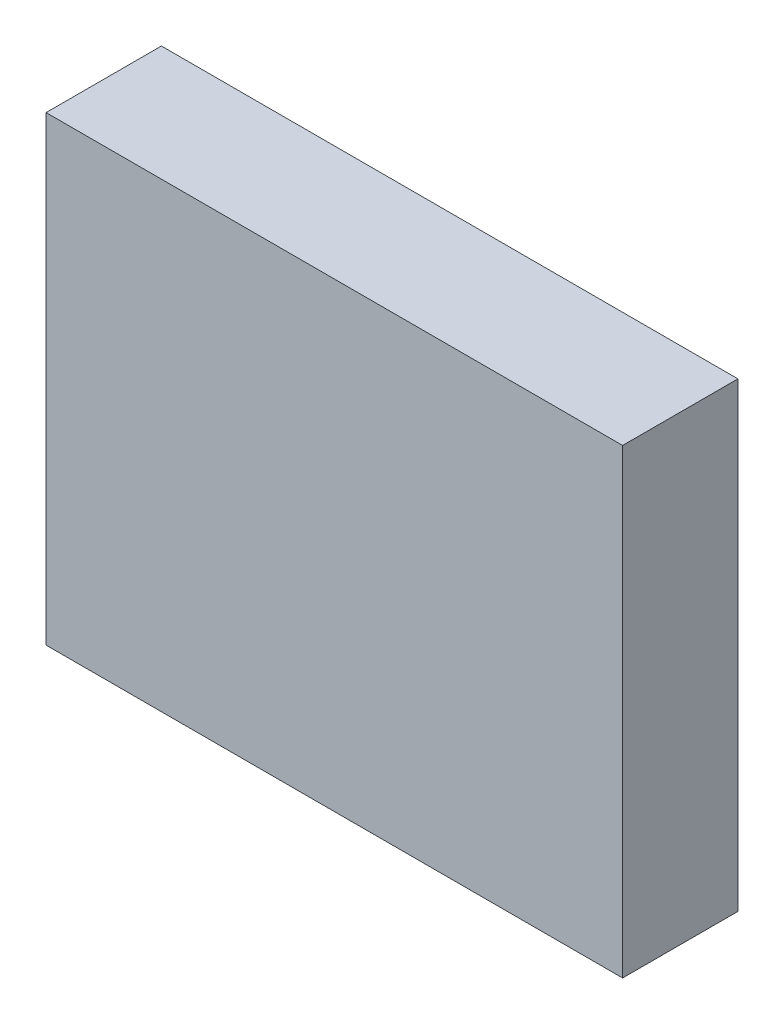
SolidWorks part; units mm, degrees
ref_plane "Front Plane" through (0, 0, 0) normal (0, 0, 1) x (1, 0, 0)
ref_plane "Top Plane" through (0, 0, 0) normal (0, 1, 0) x (1, 0, 0)
ref_plane "Right Plane" through (0, 0, 0) normal (1, 0, 0) x (0, 0, -1)
sketch "Sketch1" plane through (0, 0, 0) normal (0, 0, 1) x (1, 0, 0)
  line L1 (25, -20) -> (-25, -20)
  line L2 (25, -20) -> (25, 20)
  line L3 (25, 20) -> (-25, 20)
  line L4 (-25, -20) -> (-25, 20)
  line L5 (25, -20) -> (-25, 20) construction
  line L6 (25, 20) -> (-25, -20) construction
  point P0 (0, 0)
  dimension "D1" = 40
  dimension "D2" = 50
extrude "Boss-Extrude1" add sketch "Sketch1" along normal blind 10
